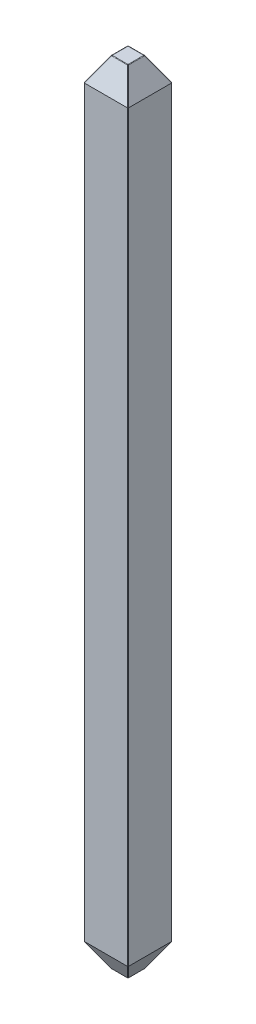
SolidWorks part; units mm, degrees
ref_plane "前视基准面" through (0, 0, 0) normal (0, 0, 1) x (1, 0, 0)
ref_plane "上视基准面" through (0, 0, 0) normal (0, 1, 0) x (1, 0, 0)
ref_plane "右视基准面" through (0, 0, 0) normal (1, 0, 0) x (0, 0, -1)
sketch "Sketch1" plane through (0, 0, 0) normal (0, 1, 0) x (1, 0, 0)
  line L1 (-0.32, 0.32) -> (0.32, 0.32)
  line L2 (-0.32, 0.32) -> (-0.32, -0.32)
  line L3 (-0.32, -0.32) -> (0.32, -0.32)
  line L4 (0.32, 0.32) -> (0.32, -0.32)
  line L5 (-0.32, 0.32) -> (0.32, -0.32) construction
  line L6 (-0.32, -0.32) -> (0.32, 0.32) construction
  point P0 (0, 0)
  dimension "D1" = 0.64
  dimension "D2" = 0.64
extrude "Boss-Extrude1" add sketch "Sketch1" along normal blind 11.5
chamfer "Chamfer1" distance 0.2 angle 60 4 edges at (0, 11.5, 0.32) (-0.32, 11.5, 0) (0, 11.5, -0.32) (0.32, 11.5, 0)
chamfer "Chamfer2" distance 0.2 angle 60 4 edges at (0, 0, -0.32) (-0.32, 0, 0) (0, 0, 0.32) (0.32, 0, 0)
fillet "Fillet2" radius 0.01 20 edges at (-0.12, 11.5, 0) (0, 11.5, 0.12) (0.12, 11.5, 0) (0, 11.5, -0.12) (0.22, 11.3268, -0.22) (-0.22, 11.3268, -0.22) (-0.22, 11.3268, 0.22) (0.22, 11.3268, 0.22) (-0.12, 0, 0) (0, 0, -0.12) (0, 0, 0.12) (0.12, 0, 0) (-0.22, 0.1732, -0.22) (-0.22, 0.1732, 0.22) (0.22, 0.1732, -0.22) (0.22, 0.1732, 0.22) (-0.32, 5.75, -0.32) (0.32, 5.75, -0.32) (0.32, 5.75, 0.32) (-0.32, 5.75, 0.32)
